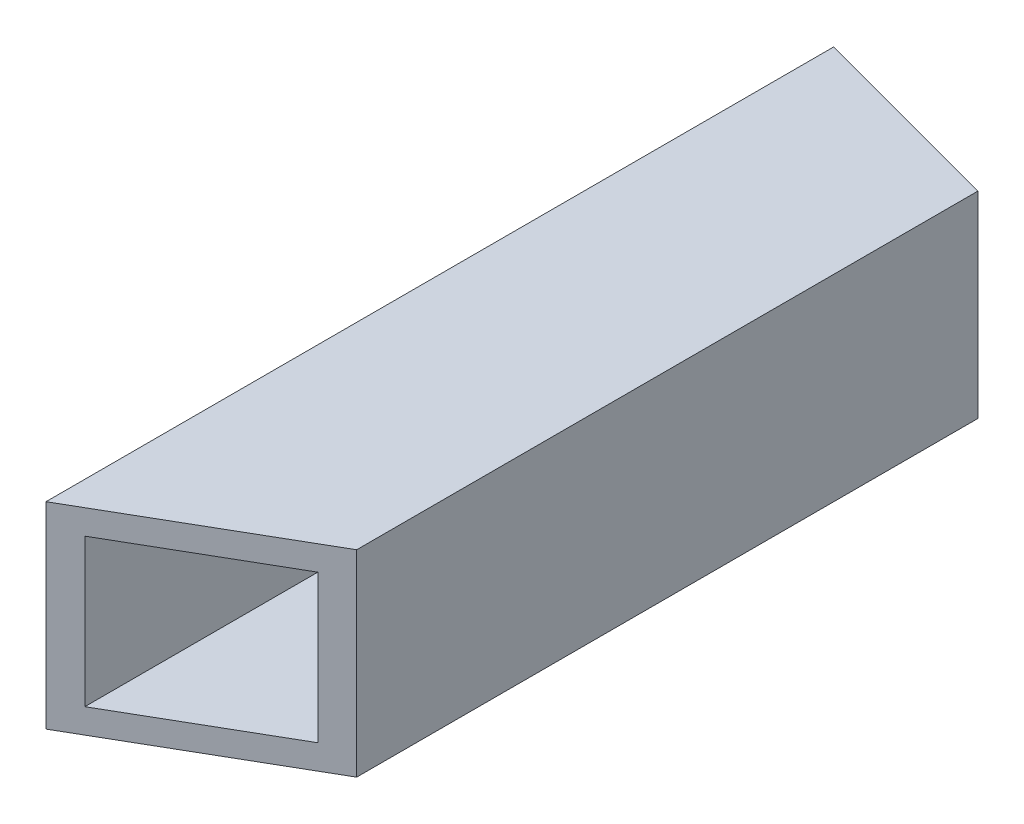
SolidWorks part; units mm, degrees
ref_plane "Front Plane" through (0, 0, 0) normal (0, 0, 1) x (1, 0, 0)
ref_plane "Top Plane" through (0, 0, 0) normal (0, 1, 0) x (1, 0, 0)
ref_plane "Right Plane" through (0, 0, 0) normal (1, 0, 0) x (0, 0, -1)
sketch "Sketch1" plane through (0, 0, 0) normal (0, 0, 1) x (1, 0, 0)
  line L1 (9.525, -9.525) -> (-9.525, -9.525)
  line L2 (9.525, -9.525) -> (9.525, 9.525)
  line L3 (9.525, 9.525) -> (-9.525, 9.525)
  line L4 (-9.525, -9.525) -> (-9.525, 9.525)
  line L5 (9.525, -9.525) -> (-9.525, 9.525) construction
  line L6 (9.525, 9.525) -> (-9.525, -9.525) construction
  line L7 (12.7, -12.7) -> (-12.7, -12.7)
  line L8 (12.7, -12.7) -> (12.7, 12.7)
  line L9 (12.7, 12.7) -> (-12.7, 12.7)
  line L10 (-12.7, -12.7) -> (-12.7, 12.7)
  line L11 (12.7, -12.7) -> (-12.7, 12.7) construction
  line L12 (12.7, 12.7) -> (-12.7, -12.7) construction
  point P0 (0, 0)
  point P6 (0, 0)
  dimension "D1" = 25.4
  dimension "D2" = 25.4
  dimension "D3" = 3.175
extrude "Boss-Extrude1" add sketch "Sketch1" along normal blind 101.6
ref_plane "Plane1" through (-0.8507, 0, 3.175) normal (0.2588, 0, -0.9659) x (0, -1, 0)
sketch "Sketch2" plane through (-0.8507, 0, 3.175) normal (0.2588, 0, -0.9659) x (0, -1, 0)
  line L0 (-12.7, 12.2673) -> (12.7, 12.2673)
  line L1 (-12.7, 12.2673) -> (12.7, 12.2673)
  line L2 (-12.7, -14.0288) -> (-12.7, 12.2673)
  line L3 (-12.7, -14.0288) -> (-12.7, 12.2673)
  line L4 (12.7, -14.0288) -> (-12.7, -14.0288)
  line L5 (12.7, -14.0288) -> (-12.7, -14.0288)
  line L6 (12.7, 12.2673) -> (12.7, -14.0288)
  line L7 (12.7, 12.2673) -> (12.7, -14.0288)
extrude "Cut-Extrude1" cut sketch "Sketch2" along normal through all
ref_plane "Plane2" through (40.8191, 0, 70.7007) normal (0.5, 0, 0.866) x (0, -1, 0)
sketch "Sketch5" plane through (40.8191, 0, 70.7007) normal (0.5, 0, 0.866) x (0, -1, 0)
  line L0 (-12.7, -61.7985) -> (12.7, -61.7985)
  line L1 (-12.7, -61.7985) -> (12.7, -61.7985)
  line L2 (-12.7, -61.7985) -> (-12.7, -32.4691)
  line L3 (-12.7, -61.7985) -> (-12.7, -32.4691)
  line L4 (-12.7, -32.4691) -> (12.7, -32.4691)
  line L5 (-12.7, -32.4691) -> (12.7, -32.4691)
  line L6 (12.7, -32.4691) -> (12.7, -61.7985)
  line L7 (12.7, -32.4691) -> (12.7, -61.7985)
extrude "Cut-Extrude2" cut sketch "Sketch5" along normal through all
